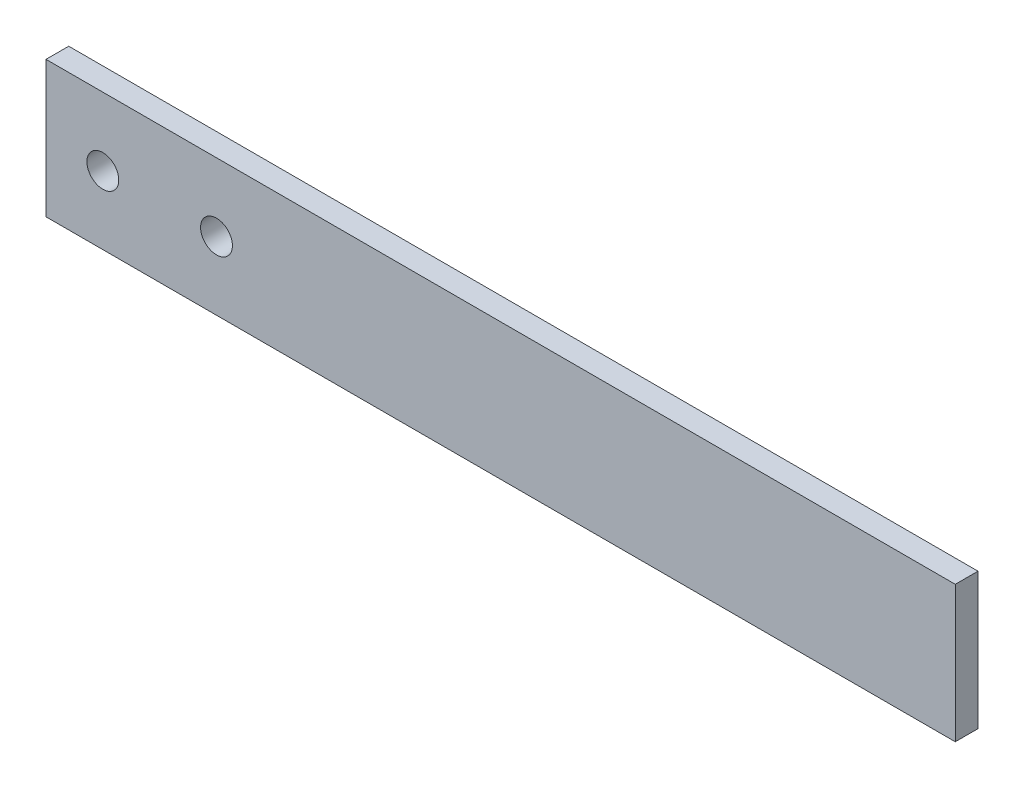
SolidWorks part; units mm, degrees
material "ASTM A36 Steel"
ref_plane "Front Plane" through (0, 0, 0) normal (0, 0, 1) x (1, 0, 0)
ref_plane "Top Plane" through (0, 0, 0) normal (0, 1, 0) x (1, 0, 0)
ref_plane "Right Plane" through (0, 0, 0) normal (1, 0, 0) x (0, 0, -1)
sketch "Sketch1" plane through (0, 0, 0) normal (0, 0, 1) x (1, 0, 0)
  line L1 (-200, -30) -> (200, -30)
  line L2 (-200, -30) -> (-200, 30)
  line L3 (-200, 30) -> (200, 30)
  line L4 (200, -30) -> (200, 30)
  line L5 (-200, -30) -> (200, 30) construction
  line L6 (-200, 30) -> (200, -30) construction
  point P0 (0, 0)
  dimension "D1" = 400
  dimension "D2" = 60
extrude "Boss-Extrude1" add sketch "Sketch1" along normal blind 10
sketch "Sketch2" plane through (0, 0, 10) normal (0, 0, 1) x (1, 0, 0)
  line L0 (-200, 30) -> (-200, -30) construction
  circle A0 centre (-175, 0) radius 7
  circle A1 centre (-125, 0) radius 7
  dimension "D1" = 14
  dimension "D2" = 25
  dimension "D3" = 14
  dimension "D4" = 50
extrude "Cut-Extrude1" cut sketch "Sketch2" against normal blind 10
